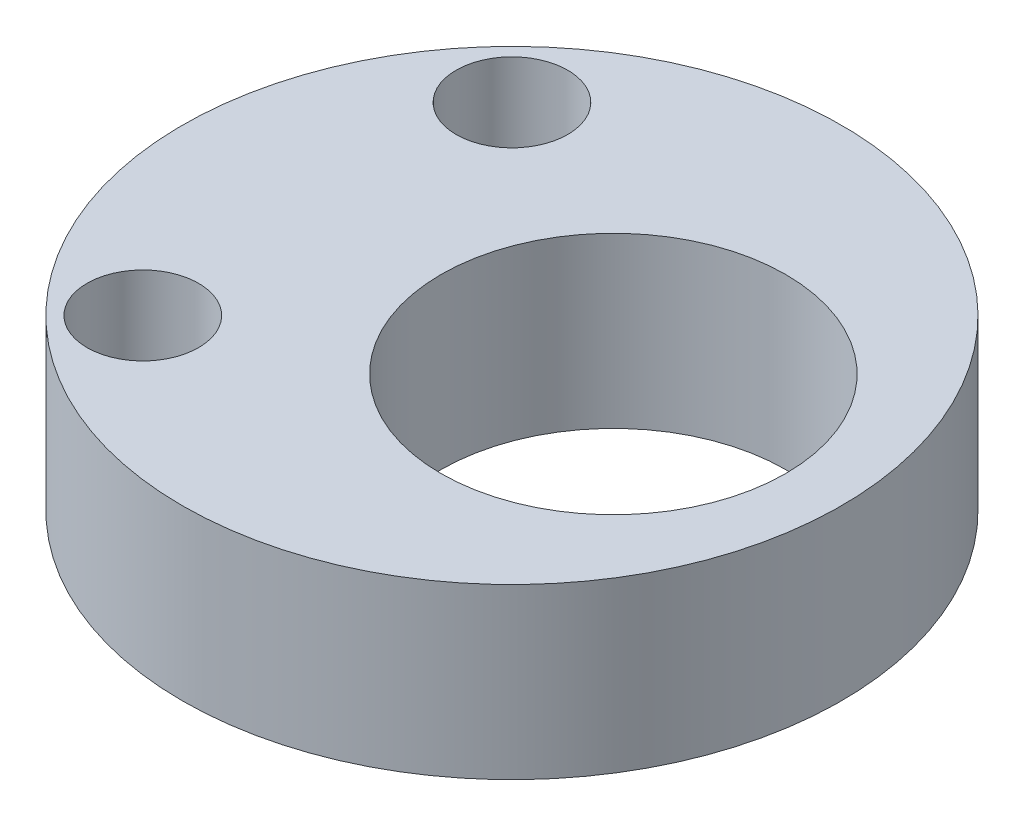
SolidWorks part; units mm, degrees
material "Brass"
ref_plane "Front Plane" through (0, 0, 0) normal (0, 0, 1) x (1, 0, 0)
ref_plane "Top Plane" through (0, 0, 0) normal (0, 1, 0) x (1, 0, 0)
ref_plane "Right Plane" through (0, 0, 0) normal (1, 0, 0) x (0, 0, -1)
sketch "Sketch1" plane through (0, 0, 0) normal (0, 1, 0) x (1, 0, 0)
  line L0 (0, 0) -> (-14.3131, 0) construction
  line L1 (0, 0) -> (17.6761, 0) construction
  line L2 (0, 0) -> (0, 18.9534) construction
  line L3 (0, 0) -> (18.7478, 0) construction
  circle A0 centre (0, 0) radius 9.75
  circle A1 centre (3, 0) radius 5.1
  circle A4 centre (-5.46, 5.46) radius 1.65
  circle A5 centre (-5.46, -5.46) radius 1.65
  point P5 (3, 0)
  point P13 (-5.46, 5.46)
  point P14 (-5.46, -5.46)
  dimension "D3" = 19.5
  dimension "D4" = 10.2
  dimension "D9" = 3.3
  dimension "D10" = 3.3
  dimension "D2" = 3
  dimension "D5" = 5.46
  dimension "D6" = 5.46
  dimension "D7" = 5.46
  dimension "D8" = 5.46
extrude "Boss-Extrude4" add sketch "Sketch1" along normal blind 5
